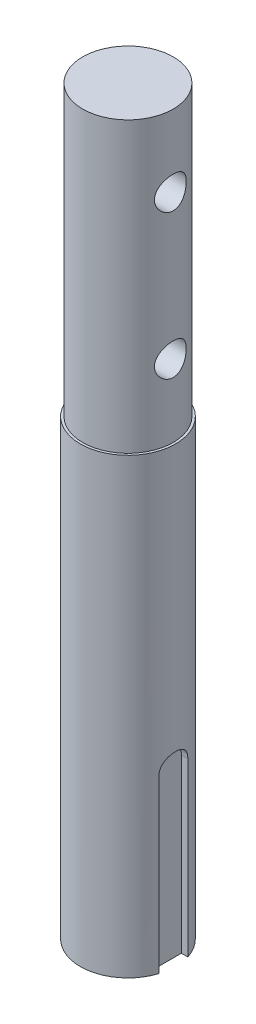
SolidWorks part; units mm, degrees
material "ASTM A36 Steel"
ref_plane "Front Plane" through (0, 0, 0) normal (0, 0, 1) x (1, 0, 0)
ref_plane "Top Plane" through (0, 0, 0) normal (0, 1, 0) x (1, 0, 0)
ref_plane "Right Plane" through (0, 0, 0) normal (1, 0, 0) x (0, 0, -1)
sketch "Sketch1" plane through (0, 0, 0) normal (0, 1, 0) x (1, 0, 0)
  circle A0 centre (0, 0) radius 33
  dimension "D1" = 66
extrude "Boss-Extrude1" add sketch "Sketch1" along normal blind 313.5
sketch "Sketch2" plane through (0, 313.5, 0) normal (0, 1, 0) x (1, 0, 0)
  circle A0 centre (0, 0) radius 31.34
  dimension "D1" = 62.68
extrude "Boss-Extrude2" add sketch "Sketch2" along normal blind 200
ref_plane "Plane1" through (33, 0, 0) normal (1, 0, 0) x (0, 0, -1)
sketch "Sketch3" plane through (33, 0, 0) normal (1, 0, 0) x (0, 0, -1)
  line L0 (-10, 119) -> (-10, 0)
  line L1 (-33, 0) -> (33, 0) construction
  line L2 (10, 119) -> (10, 0)
  line L3 (10, 0) -> (-10, 0)
  arc A0 (10, 119) -> (-10, 119) centre (0, 119) ccw
  point P1 (0, 119)
  dimension "D1" = 20
  dimension "D2" = 119
extrude "Cut-Extrude1" cut sketch "Sketch3" against normal blind 6
sketch "Sketch5" plane through (0, 0, 0) normal (1, 0, 0) x (0, 0, -1)
  line L0 (31.34, 513.5) -> (-31.34, 513.5) construction
  circle A0 centre (0, 463.5) radius 11
  circle A1 centre (0, 363.5) radius 11
  dimension "D1" = 22
  dimension "D2" = 22
  dimension "D3" = 50
  dimension "D4" = 100
extrude "Cut-Extrude2" cut sketch "Sketch5" against normal through all both and the other way through all
